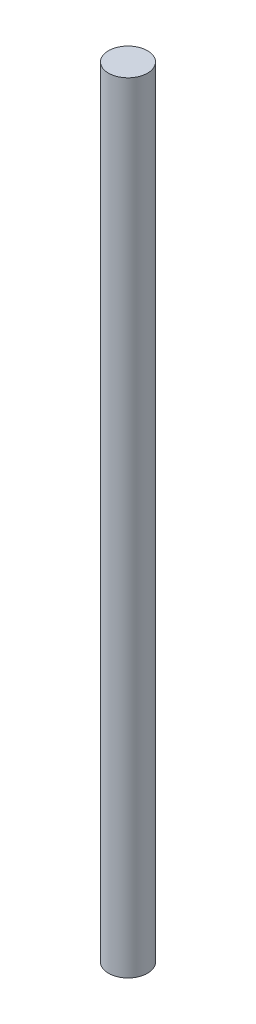
SolidWorks part; units mm, degrees
ref_plane "Front Plane" through (0, 0, 0) normal (0, 0, 1) x (1, 0, 0)
ref_plane "Top Plane" through (0, 0, 0) normal (0, 1, 0) x (1, 0, 0)
ref_plane "Right Plane" through (0, 0, 0) normal (1, 0, 0) x (0, 0, -1)
sketch "Sketch1" plane through (0, 0, 0) normal (0, 1, 0) x (1, 0, 0)
  circle A0 centre (0, 0) radius 3.5
  dimension "D1" = 7
extrude "Boss-Extrude1" add sketch "Sketch1" along normal blind 140
